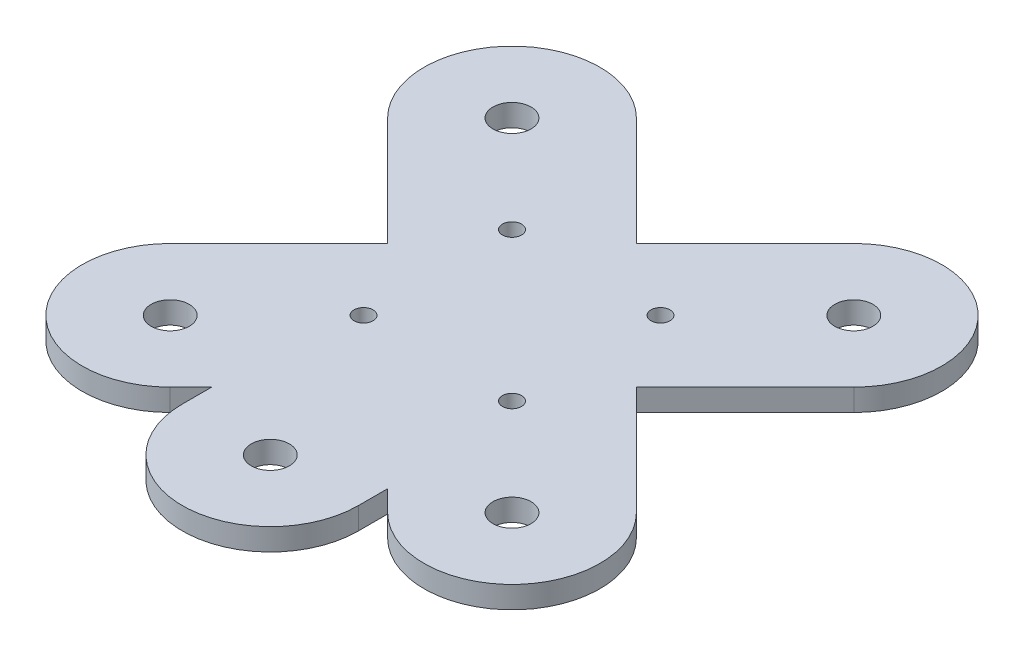
SolidWorks part; units mm, degrees
ref_plane "Front" through (0, 0, 0) normal (0, 0, 1) x (1, 0, 0)
ref_plane "Top" through (0, 0, 0) normal (0, 1, 0) x (1, 0, 0)
ref_plane "Right" through (0, 0, 0) normal (1, 0, 0) x (0, 0, -1)
sketch "Esquisse2" plane through (0, 0, 0) normal (0, 1, 0) x (1, 0, 0)
  line L0 (-30, 30) -> (30, -30) construction
  line L1 (30, 30) -> (30, -30) construction
  line L2 (30, -30) -> (-30, -30) construction
  line L3 (-30, -30) -> (-30, 30) construction
  line L4 (-30, 30) -> (30, 30) construction
  line L5 (30, 30) -> (-30, -30) construction
  line L6 (-1.7157, 1.7157) -> (-58.2843, 58.2843) construction
  line L7 (-22.9289, -19.4975) -> (-79.4975, 37.0711)
  line L8 (19.4975, 22.9289) -> (-37.0711, 79.4975)
  line L11 (5, 11.5685) -> (5, 91.5685) construction
  line L15 (1.7157, 1.7157) -> (58.2843, 58.2843) construction
  line L16 (-19.4975, 22.9289) -> (37.0711, 79.4975)
  line L17 (21.5685, -5) -> (101.5685, -5) construction
  line L20 (22.9289, -19.4975) -> (79.4975, 37.0711)
  line L28 (1.7157, -1.7157) -> (58.2843, -58.2843) construction
  line L29 (-11.5685, -5) -> (-91.5685, -5) construction
  line L30 (22.9289, 19.4975) -> (79.4975, -37.0711)
  line L31 (-19.4975, -22.9289) -> (37.0711, -79.4975)
  line L32 (0, -2.4264) -> (0, -82.4264) construction
  line L33 (30, -2.4264) -> (30, -82.4264)
  line L34 (-30, -2.4264) -> (-30, -82.4264)
  line L35 (-1.7157, -1.7157) -> (-58.2843, -58.2843) construction
  line L36 (19.4975, -22.9289) -> (-37.0711, -79.4975)
  line L37 (-22.9289, 19.4975) -> (-79.4975, -37.0711)
  line L59 (0, 2.4264) -> (0, 82.4264) construction
  line L60 (-30, 2.4264) -> (-30, 82.4264)
  line L61 (30, 2.4264) -> (30, 82.4264)
  line L62 (2.4264, 0) -> (82.4264, 0) construction
  line L63 (2.4264, 30) -> (82.4264, 30)
  line L64 (2.4264, -30) -> (82.4264, -30)
  line L65 (-2.4264, 0) -> (-82.4264, 0) construction
  line L66 (-2.4264, -30) -> (-82.4264, -30)
  line L67 (-2.4264, 30) -> (-82.4264, 30)
  line L68 (0, 2.4264) -> (0, 82.4264) construction
  line L69 (-30, 2.4264) -> (-30, 82.4264)
  line L70 (30, 2.4264) -> (30, 82.4264)
  line L71 (2.4264, 0) -> (82.4264, 0) construction
  line L72 (2.4264, 30) -> (82.4264, 30)
  line L73 (2.4264, -30) -> (82.4264, -30)
  line L74 (-2.4264, 0) -> (-82.4264, 0) construction
  line L75 (-2.4264, -30) -> (-82.4264, -30)
  line L76 (-2.4264, 30) -> (-82.4264, 30)
  arc A0 (-22.9289, -19.4975) -> (19.4975, 22.9289) centre (-1.7157, 1.7157) ccw
  arc A1 (-37.0711, 79.4975) -> (-79.4975, 37.0711) centre (-58.2843, 58.2843) ccw
  arc A6 (-19.4975, 22.9289) -> (22.9289, -19.4975) centre (1.7157, 1.7157) ccw
  arc A7 (79.4975, 37.0711) -> (37.0711, 79.4975) centre (58.2843, 58.2843) ccw
  arc A16 (22.9289, 19.4975) -> (-19.4975, -22.9289) centre (1.7157, -1.7157) ccw
  arc A17 (37.0711, -79.4975) -> (79.4975, -37.0711) centre (58.2843, -58.2843) ccw
  arc A18 (30, -2.4264) -> (-30, -2.4264) centre (0, -2.4264) ccw
  arc A19 (-30, -82.4264) -> (30, -82.4264) centre (0, -82.4264) ccw
  arc A20 (19.4975, -22.9289) -> (-22.9289, 19.4975) centre (-1.7157, -1.7157) ccw
  arc A21 (-79.4975, -37.0711) -> (-37.0711, -79.4975) centre (-58.2843, -58.2843) ccw
  arc A42 (-30, 2.4264) -> (30, 2.4264) centre (0, 2.4264) ccw
  arc A43 (30, 82.4264) -> (-30, 82.4264) centre (0, 82.4264) ccw
  arc A44 (2.4264, 30) -> (2.4264, -30) centre (2.4264, 0) ccw
  arc A45 (82.4264, -30) -> (82.4264, 30) centre (82.4264, 0) ccw
  arc A46 (-2.4264, -30) -> (-2.4264, 30) centre (-2.4264, 0) ccw
  arc A47 (-82.4264, 30) -> (-82.4264, -30) centre (-82.4264, 0) ccw
  point P0 (0, 0)
  point P9 (-30, 30)
  point P19 (5, 51.5685)
  point P22 (0, 49.4975)
  point P29 (30, 30)
  point P33 (61.5685, -5)
  point P39 (49.4975, 0)
  point P46 (30, -30)
  point P53 (0, -42.4264)
  point P61 (-51.5685, -5)
  point P63 (-30, -30)
  point P66 (5, -5)
  point P71 (-49.4975, 0)
  point P76 (0, 0)
  point P109 (0, 49.4975)
  point P116 (49.4975, 0)
  point P123 (-49.4975, 0)
  point P130 (0, 42.4264)
  point P137 (42.4264, 0)
  point P144 (-42.4264, 0)
  point P151 (0, 42.4264)
  point P158 (42.4264, 0)
  point P165 (-42.4264, 0)
  point P172 (0, 42.4264)
  point P179 (42.4264, 0)
  point P186 (-42.4264, 0)
  dimension "D4" = 30
  dimension "D1" = 60
  dimension "D2" = 60
  dimension "D3" = 80
  dimension "D5" = 8
extrude "Boss.-Extru.1" add sketch "Esquisse2" along normal blind 7.5
sketch "Esquisse4" plane through (0, 0, 0) normal (0, -1, 0) x (-1, 0, 0)
  line L0 (0, 0) -> (-79.4975, -79.4975) construction
  line L1 (-25.317, -46.5302) -> (-7.6393, -28.8525)
  line L2 (-7.6393, -28.8525) -> (-28.8525, -7.6393)
  line L3 (-28.8525, -7.6393) -> (-46.5302, -25.317)
  line L4 (-42.4264, 0) -> (-79.4975, -37.0711) construction
  line L5 (-46.5302, 25.317) -> (-28.8525, 7.6393)
  line L6 (-7.6393, 28.8525) -> (-25.317, 46.5302)
  line L7 (-28.8525, 7.6393) -> (-7.6393, 28.8525)
  line L8 (25.317, 46.5302) -> (7.6393, 28.8525)
  line L9 (28.8525, 7.6393) -> (46.5302, 25.317)
  line L10 (7.6393, 28.8525) -> (28.8525, 7.6393)
  line L11 (46.5302, -25.317) -> (28.8525, -7.6393)
  line L12 (7.6393, -28.8525) -> (25.317, -46.5302)
  line L13 (28.8525, -7.6393) -> (7.6393, -28.8525)
  arc A0 (-79.4975, -37.0711) -> (-37.0711, -79.4975) centre (-58.2843, -58.2843) ccw construction
  arc A1 (-25.317, -46.5302) -> (-46.5302, -25.317) centre (-58.2843, -58.2843) ccw
  arc A2 (-46.5302, 25.317) -> (-25.317, 46.5302) centre (-58.2843, 58.2843) ccw
  arc A3 (25.317, 46.5302) -> (46.5302, 25.317) centre (58.2843, 58.2843) ccw
  arc A4 (46.5302, -25.317) -> (25.317, -46.5302) centre (58.2843, -58.2843) ccw
  point P36 (0, 0)
  dimension "D5" = 35
  dimension "D1" = 25
  dimension "D2" = 25
  dimension "D3" = 15
  dimension "D4" = 30
extrude "Enlèv. mat.-Extru.1" cut sketch "Esquisse4" against normal blind 2 contours L0 L2 L3 A1 | L2 L0 A1 L1 | A2 L5 L7 L6 | A3 L8 L10 L9 | A4 L11 L13 L12
sketch "Esquisse5" plane through (0, 2, 0) normal (0, -1, 0) x (-1, 0, 0)
  line L0 (0, 0) -> (-58.2843, -58.2843) construction
  line L1 (-58.2843, -58.2843) -> (0, 0) construction
  line L2 (-7.6393, -28.8525) -> (-28.8525, -7.6393) construction
  circle A0 centre (-25.317, -25.317) radius 3.25
  circle A1 centre (-25.317, 25.317) radius 3.25
  circle A2 centre (25.317, 25.317) radius 3.25
  circle A3 centre (25.317, -25.317) radius 3.25
  point P17 (0, 0)
  dimension "D1" = 6.5
  dimension "D2" = 10
extrude "Enlèv. mat.-Extru.2" cut sketch "Esquisse5" against normal through all
sketch "Esquisse7" plane through (0, 0, 0) normal (0, -1, 0) x (-1, 0, 0)
  circle A0 centre (0, -82.4264) radius 6.5
  circle A1 centre (-58.2843, -58.2843) radius 6.5
  circle A2 centre (-82.4264, 0) radius 6.5 [skipped]
  circle A3 centre (-58.2843, 58.2843) radius 6.5
  circle A4 centre (0, 82.4264) radius 6.5 [skipped]
  circle A5 centre (58.2843, 58.2843) radius 6.5
  circle A6 centre (82.4264, 0) radius 6.5 [skipped]
  circle A7 centre (58.2843, -58.2843) radius 6.5
  point P20 (0, 0)
  dimension "D1" = 13
extrude "Enlèv. mat.-Extru.3" cut sketch "Esquisse7" against normal through all
